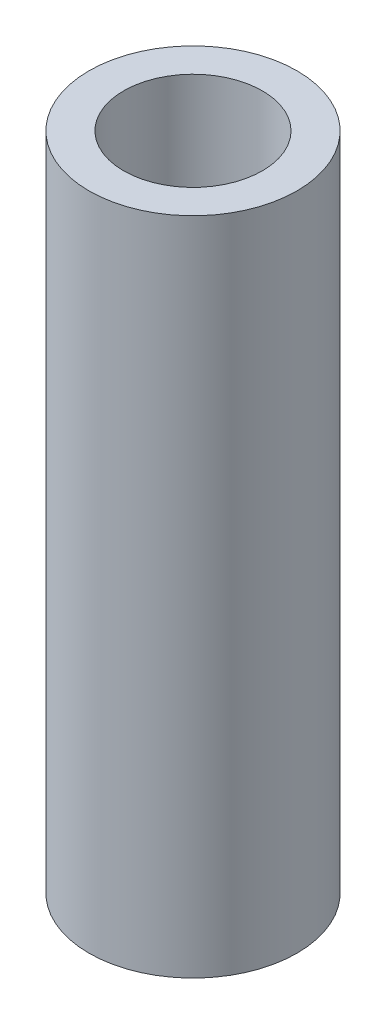
SolidWorks part; units mm, degrees
material "6061-T6 (SS)"
ref_plane "Front Plane" through (0, 0, 0) normal (0, 0, 1) x (1, 0, 0)
ref_plane "Top Plane" through (0, 0, 0) normal (0, 1, 0) x (1, 0, 0)
ref_plane "Right Plane" through (0, 0, 0) normal (1, 0, 0) x (0, 0, -1)
sketch "Sketch1" plane through (0, 0, 0) normal (0, 1, 0) x (1, 0, 0)
  circle A0 centre (0, 0) radius 4.7625
  circle A1 centre (0, 0) radius 3.175
  dimension "D1" = 9.525
  dimension "D2" = 6.35
extrude "Boss-Extrude1" add sketch "Sketch1" along normal blind 30.226
